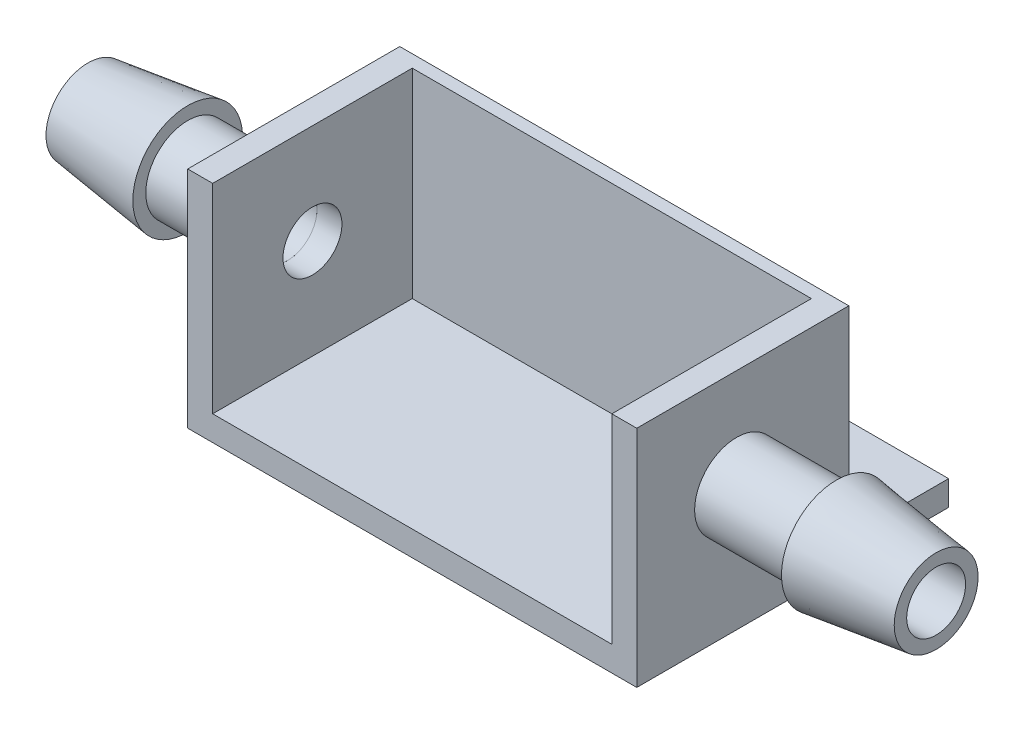
SolidWorks part; units mm, degrees
ref_plane "Front Plane" through (0, 0, 0) normal (0, 0, 1) x (1, 0, 0)
ref_plane "Top Plane" through (0, 0, 0) normal (0, 1, 0) x (1, 0, 0)
ref_plane "Right Plane" through (0, 0, 0) normal (1, 0, 0) x (0, 0, -1)
sketch "Sketch1" plane through (0, 0, 0) normal (0, 0, 1) x (1, 0, 0)
  line L1 (-57.15, 0) -> (57.15, 0)
  line L2 (-57.15, 0) -> (-57.15, 6.35)
  line L3 (-50.8, 6.35) -> (50.8, 6.35)
  line L4 (57.15, 0) -> (57.15, 6.35)
  line L6 (-57.15, 6.35) -> (-57.15, 57.15)
  line L7 (-57.15, 57.15) -> (-50.8, 57.15)
  line L8 (-50.8, 6.35) -> (-50.8, 57.15)
  line L10 (57.15, 6.35) -> (57.15, 57.15)
  line L11 (57.15, 57.15) -> (50.8, 57.15)
  line L12 (50.8, 6.35) -> (50.8, 57.15)
  point P10 (-57.15, 117.0248)
  point P11 (57.15, 111.2725)
  point P13 (0, 0)
  dimension "D1" = 6.35
  dimension "D2" = 101.6
  dimension "D3" = 6.35
  dimension "D4" = 50.8
extrude "Boss-Extrude1" add sketch "Sketch1" along normal mid plane 50.8
sketch "Sketch2" plane through (0, 0, -25.4) normal (0, 0, -1) x (-1, 0, 0)
  line L0 (57.15, 0) -> (-57.15, 0) construction
  line L1 (-57.15, 57.15) -> (57.15, 57.15)
  line L2 (-57.15, 57.15) -> (-57.15, 0)
  line L3 (-57.15, 0) -> (57.15, 0)
  line L4 (57.15, 57.15) -> (57.15, 0)
extrude "Boss-Extrude2" add sketch "Sketch2" along normal blind 3.175
sketch "Sketch4" plane through (0, 0, 0) normal (0, 0, 1) x (1, 0, 0)
  line L0 (-76.2, 31.75) -> (76.2, 31.75) construction
  line L1 (0, 31.75) -> (0, 0) construction
  line L2 (57.15, 39.25) -> (57.15, 42.425)
  line L3 (-50.8, 6.35) -> (-50.8, 57.15) construction
  line L4 (-57.15, 42.425) -> (-82.55, 42.425)
  line L5 (-57.15, 57.15) -> (-57.15, 0) construction
  line L6 (-82.55, 42.425) -> (-82.55, 45.72)
  line L7 (-82.55, 45.72) -> (-107.95, 42.425)
  line L8 (-107.95, 42.425) -> (-107.95, 39.25)
  line L9 (-107.95, 39.25) -> (-57.15, 39.25)
  line L10 (-57.15, 39.25) -> (-57.15, 42.425)
  line L11 (107.95, 39.25) -> (57.15, 39.25)
  line L12 (107.95, 42.425) -> (107.95, 39.25)
  line L13 (82.55, 45.72) -> (107.95, 42.425)
  line L14 (82.55, 42.425) -> (82.55, 45.72)
  line L15 (57.15, 42.425) -> (82.55, 42.425)
  point P3 (-50.8, 31.75)
  dimension "D1" = 7.5
  dimension "D2" = 25.4
  dimension "D3" = 3.175
  dimension "D4" = 25.4
  dimension "D5" = 13.97
revolve "Revolve1" add sketch "Sketch4" angle 360 about L0
sketch "Sketch3" plane through (0, 0, 0) normal (1, 0, 0) x (0, 0, -1)
  line L0 (-25.4, 57.15) -> (28.575, 57.15) construction
  circle A0 centre (0, 31.75) radius 7.5
  dimension "D2" = 15
  dimension "D1" = 25.4
extrude "Cut-Extrude2" cut sketch "Sketch3" against normal through all both and the other way through all
sketch "Sketch5" plane through (0, 0, 0) normal (0, -1, 0) x (1, 0, 0)
  line L1 (-57.15, -28.575) -> (57.15, -28.575)
  line L2 (-57.15, -28.575) -> (-57.15, -53.975)
  line L3 (-57.15, -53.975) -> (57.15, -53.975)
  line L4 (57.15, -28.575) -> (57.15, -53.975)
  circle A0 centre (38.1, -41.275) radius 3.4925
  circle A1 centre (12.7, -41.275) radius 3.4925
  circle A2 centre (-12.7, -41.275) radius 3.4925
  circle A3 centre (-38.1, -41.275) radius 3.4925
  point P9 (57.15, -41.275)
  dimension "D2" = 6.985
  dimension "D1" = 25.4
  dimension "D3" = 19.05
  dimension "D4" = 4
extrude "Boss-Extrude3" add sketch "Sketch5" against normal blind 6.35
